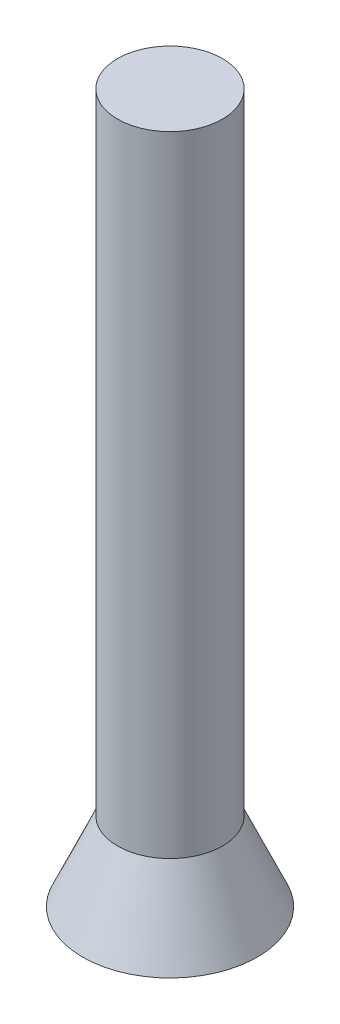
SolidWorks part; units mm, degrees
ref_plane "Front Plane" through (0, 0, 0) normal (0, 0, 1) x (1, 0, 0)
ref_plane "Top Plane" through (0, 0, 0) normal (0, 1, 0) x (1, 0, 0)
ref_plane "Right Plane" through (0, 0, 0) normal (1, 0, 0) x (0, 0, -1)
sketch "Sketch1" plane through (0, 0, 0) normal (0, 1, 0) x (1, 0, 0)
  circle A0 centre (0, 0) radius 2.5
extrude "Boss-Extrude1" add sketch "Sketch1" along normal blind 2.25 draft 24
sketch "Sketch2" plane through (0, 2.25, 0) normal (0, 1, 0) x (1, 0, 0)
  circle A0 centre (0, 0) radius 1.5
extrude "Boss-Extrude2" add sketch "Sketch2" along normal blind 18
sketch "Sketch3" plane through (0, 0, 0) normal (0, -1, 0) x (-1, 0, 0)
  line L0 (0, 0) -> (0, -1.6875) construction
  line L1 (0, 0) -> (-3.4963, 0) construction
  line L2 (-0.5, 0.5) -> (-0.5, 2)
  line L3 (0.5, -2) -> (-0.5, -2)
  line L4 (0.5, -2) -> (0.5, -0.5)
  line L5 (0.5, 2) -> (-0.5, 2)
  line L6 (-0.5, -2) -> (-0.5, -0.5)
  line L7 (0.5, -2) -> (-0.5, 2) construction
  line L8 (0.5, 2) -> (-0.5, -2) construction
  line L9 (2, -0.5) -> (0.5, -0.5)
  line L10 (2, -0.5) -> (2, 0.5)
  line L11 (2, 0.5) -> (0.5, 0.5)
  line L12 (-2, -0.5) -> (-2, 0.5)
  line L13 (2, -0.5) -> (-2, 0.5) construction
  line L14 (2, 0.5) -> (-2, -0.5) construction
  line L15 (0.5, 0.5) -> (0.5, 2)
  line L16 (-0.5, -0.5) -> (-2, -0.5)
  line L17 (-0.5, 0.5) -> (-2, 0.5)
  point P4 (0, 0)
  point P12 (0, 0)
extrude "Cut-Extrude1" cut sketch "Sketch3" against normal blind 1.5 draft 16.5
